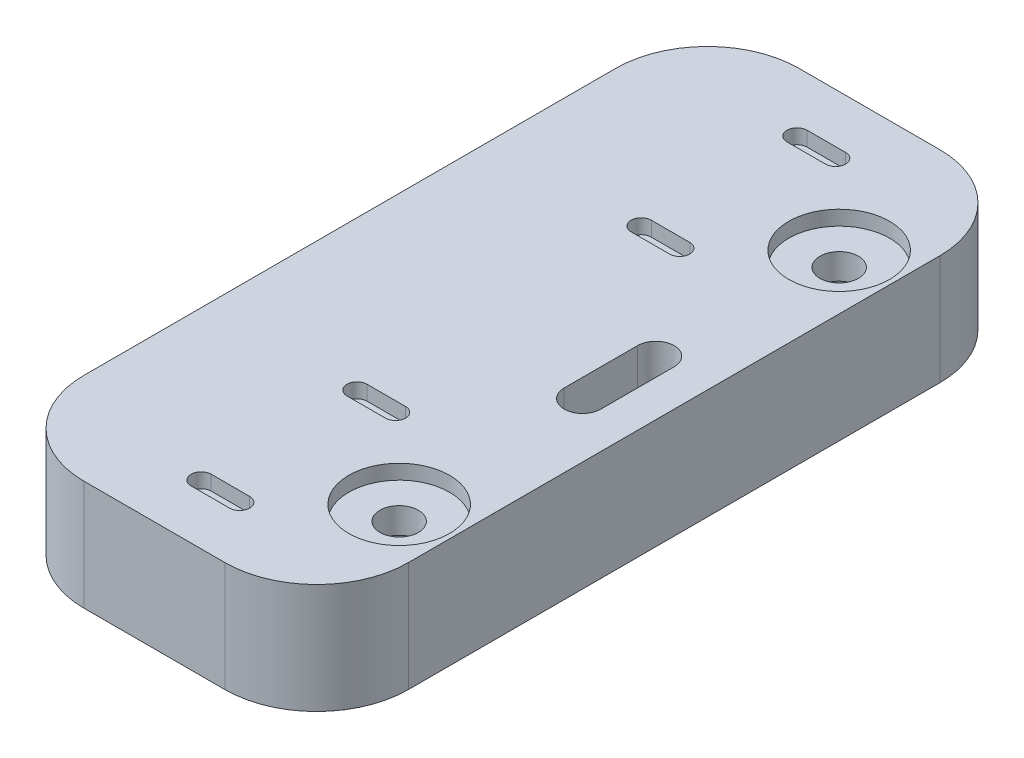
SolidWorks part; units mm, degrees
material "Acrylic (Medium-high impact)"
ref_plane "Front Plane" through (0, 0, 0) normal (0, 0, 1) x (1, 0, 0)
ref_plane "Top Plane" through (0, 0, 0) normal (0, 1, 0) x (1, 0, 0)
ref_plane "Right Plane" through (0, 0, 0) normal (1, 0, 0) x (0, 0, -1)
sketch "Sketch1" plane through (0, 0, 0) normal (0, 1, 0) x (1, 0, 0)
  line L0 (32.3833, 19.5) -> (1.2064, 19.5)
  line L1 (1.2064, -19.5) -> (32.3833, -19.5)
  line L3 (21.125, 36.5896) -> (17.5, 30.3109) construction
  line L4 (0, 0) -> (17.5, -30.3109) construction
  line L6 (14.6917, 19.5) -> (14.6917, -19.5)
  line L7 (9.8667, 43.0896) -> (32.3833, 30.0896)
  line L8 (29.3833, 12) -> (29.3833, -12) construction
  line L9 (9.7058, 34.8109) -> (25.2942, 25.8109) construction
  line L10 (25.2942, -25.8109) -> (9.7058, -34.8109) construction
  line L11 (1.2064, 25.305) -> (1.2064, -25.305)
  line L12 (17.5, 30.3109) -> (0, 0) construction
  line L15 (0, 0) -> (29.3833, 0) construction
  line L16 (32.3833, 30.0896) -> (32.3833, -30.0896)
  line L17 (32.3833, -30.0896) -> (9.8667, -43.0896)
  line L23 (9.8667, 43.0896) -> (1.2064, 38.0896)
  line L24 (9.8667, -43.0896) -> (1.2064, -38.0896)
  line L25 (1.2064, 38.0896) -> (1.2064, 25.305)
  line L28 (1.2064, -38.0896) -> (1.2064, -25.305)
  line L35 (14.4288, 36.9915) -> (24.8212, 30.9915) construction
  line L60 (29.3833, -2) -> (29.3833, 2) construction
  line L61 (28.3833, -2) -> (28.3833, 2)
  line L62 (30.3833, -2) -> (30.3833, 2)
  line L69 (5.2064, -28.305) -> (5.2064, 0) construction
  line L70 (5.2064, 0) -> (5.2064, 28.305) construction
  circle A6 centre (29.3833, 12) radius 1.05
  circle A8 centre (29.3833, -12) radius 1.05
  arc A9 (28.3833, -2) -> (30.3833, -2) centre (29.3833, -2) ccw
  arc A16 (30.3833, 2) -> (28.3833, 2) centre (29.3833, 2) ccw
  point P85 (0, 0)
  point P92 (14.6917, 0)
  point P93 (0, 0)
  point P95 (29.3833, 0)
  point P148 (0, 0)
  dimension "D7" = 12
  dimension "D9" = 26
  dimension "D8" = 2.1
  dimension "D11" = 35
  dimension "D12" = 3
  dimension "D23" = 2
  dimension "D1" = 18
  dimension "D3" = 7.25
  dimension "D4" = 120
  dimension "D5" = 39
  dimension "D15" = 10
  dimension "D18" = 12
  dimension "D22" = 42.25
  dimension "D24" = 4
extrude "Boss-Extrude1" add sketch "Sketch1" along normal blind 6
hole_wizard "Ø1.6 (1.6) Diameter Hole1" positions "Sketch5" profile "Sketch4" hole size "Ø1.6" standard "ISO"
sketch "Sketch5" plane through (0, 0, 0) normal (0, -1, 0) x (-1, 0, 0)
  line L7 (9.75, -13.5) -> (-22.25, -13.5) construction
  line L11 (-6.25, -13.5) -> (-6.25, 13.5) construction
  line L13 (-6.25, -13.5) -> (-6.25, -19.5) construction
  line L15 (-6.25, 13.5) -> (-6.25, 19.5) construction
  line L16 (9.75, 13.5) -> (-22.25, 13.5) construction
  point P0 (9.75, -13.5)
  point P2 (9.75, 13.5)
  point P4 (-22.25, -13.5)
  point P6 (-22.25, 13.5)
  dimension "D1" = 27
  dimension "D2" = 32
sketch "Sketch4" plane through (-9.75, 0, 13.5) normal (1, 0, 0) x (0, 0, -1)
  line L0 (0, 0) -> (0, 6)
  line L1 (0, 6) -> (0.8, 6)
  line L2 (0.8, 6) -> (0.8, 0)
  line L5 (0.8, 0) -> (0, 0)
  line L11 (0, -6.35) -> (0, 107.95) construction
  dimension "Thru Hole Dia." = 1.6
  dimension "Thru Hole Depth" = 6
sketch "Sketch6" plane through (0, 0, 0) normal (0, -1, 0) x (-1, 0, 0)
  line L0 (0, 0) -> (32.3833, 0) construction
  line L1 (-30.6333, -9.8349) -> (-30.3083, -10.3979)
  line L2 (-17.3179, -2.8979) -> (-30.3083, -10.3979)
  line L3 (-17.6429, -2.3349) -> (-30.6333, -9.8349)
  line L4 (-17.6429, -2.3349) -> (-17.3179, -2.8979)
  line L5 (-29.3833, -12) -> (-14.6917, -12) construction
  line L6 (-32.3833, 19.5) -> (-32.3833, -19.5) construction
  line L7 (-29.3833, 12) -> (-14.6917, 12) construction
  line L8 (-30.6333, 9.8349) -> (-30.3083, 10.3979)
  line L9 (-17.3179, 2.8979) -> (-30.3083, 10.3979)
  line L10 (-17.6429, 2.3349) -> (-17.3179, 2.8979)
  line L11 (-17.6429, 2.3349) -> (-30.6333, 9.8349)
  line L12 (-14.6917, 19.5) -> (-14.6917, -19.5) construction
  circle A0 centre (-29.3833, -12) radius 2.5
  circle A1 centre (-29.3833, 12) radius 2.5
  circle M96 centre (-29.3833, 12) radius 1.05
  circle M97 centre (-29.3833, -12) radius 1.05
  dimension "D1" = 5
  dimension "D2" = 15
  dimension "D3" = 60
  dimension "D4" = 0.65
extrude "Cut-Extrude1" cut sketch "Sketch6" against normal blind 3.8 contours A1 L8 L9 M96 | L9 A1 L11 L3 L4 L10 | A0 L2 L4 L10 L11 L3 | L1 A0 L2 M97 | L11 L10 L4 L3 | L2 A0 L1 | A1 L9 L8
fillet "Fillet1" radius 5 2 edges at (32.3833, 3, -19.5) (32.3833, 3, 19.5)
fillet "Fillet2" radius 5 2 edges at (14.6917, 3, 19.5) (14.6917, 3, -19.5)
sketch "Sketch7" plane through (0, 6, 0) normal (0, 1, 0) x (1, 0, 0)
  line L0 (23.8833, 16.25) -> (23.8833, 7.75) construction
  line L1 (22.8333, 16.25) -> (24.9333, 16.25) construction
  line L2 (22.8333, 16.8) -> (24.9333, 16.8)
  line L3 (22.8333, 15.7) -> (24.9333, 15.7)
  line L4 (23.8833, 12) -> (17.5789, 12) construction
  line L5 (32.3833, 0) -> (14.6917, 0) construction
  line L6 (32.3833, 14.5) -> (32.3833, -14.5) construction
  line L7 (14.6917, 14.5) -> (14.6917, -14.5) construction
  line L8 (22.8333, 7.75) -> (24.9333, 7.75) construction
  line L9 (22.8333, 7.2) -> (24.9333, 7.2)
  line L10 (22.8333, 8.3) -> (24.9333, 8.3)
  line L11 (23.8833, -12) -> (17.5789, -12) construction
  line L12 (23.8833, -16.25) -> (23.8833, -7.75) construction
  line L13 (22.8333, -7.75) -> (24.9333, -7.75) construction
  line L14 (22.8333, -7.2) -> (24.9333, -7.2)
  line L15 (22.8333, -8.3) -> (24.9333, -8.3)
  line L16 (22.8333, -16.25) -> (24.9333, -16.25) construction
  line L17 (22.8333, -16.8) -> (24.9333, -16.8)
  line L18 (22.8333, -15.7) -> (24.9333, -15.7)
  circle A0 centre (29.3833, 12) radius 2.75
  arc A4 (22.8333, 16.8) -> (22.8333, 15.7) centre (22.8333, 16.25) ccw
  arc A5 (24.9333, 15.7) -> (24.9333, 16.8) centre (24.9333, 16.25) ccw
  arc A6 (22.8333, 7.2) -> (22.8333, 8.3) centre (22.8333, 7.75) cw
  arc A7 (24.9333, 8.3) -> (24.9333, 7.2) centre (24.9333, 7.75) cw
  circle A8 centre (29.3833, -12) radius 2.75
  arc A9 (22.8333, -7.2) -> (22.8333, -8.3) centre (22.8333, -7.75) ccw
  arc A10 (24.9333, -8.3) -> (24.9333, -7.2) centre (24.9333, -7.75) ccw
  arc A11 (22.8333, -16.8) -> (22.8333, -15.7) centre (22.8333, -16.25) cw
  arc A12 (24.9333, -15.7) -> (24.9333, -16.8) centre (24.9333, -16.25) cw
  point P10 (23.8833, 16.25)
  point P11 (23.8833, 12)
  point P26 (23.8833, 7.75)
  point P37 (23.8833, -7.75)
  point P44 (23.8833, -16.25)
  dimension "D1" = 5.5
  dimension "D3" = 8.5
  dimension "D4" = 2.1
  dimension "D5" = 0.55
  dimension "D6" = 5.5
extrude "Cut-Extrude2" cut sketch "Sketch7" against normal blind 0.8
